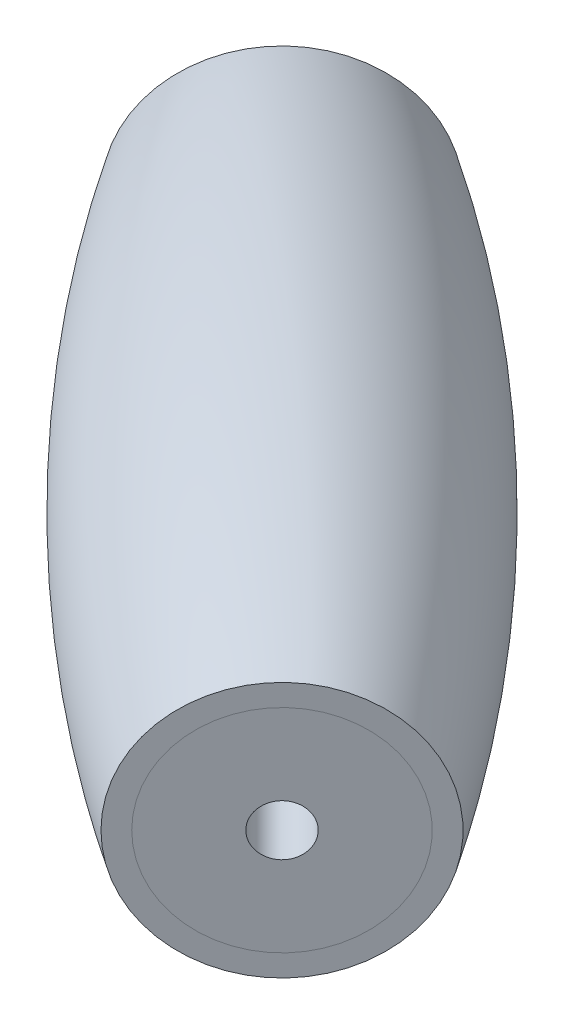
SolidWorks part; units mm, degrees
ref_plane "Front Plane" through (0, 0, 0) normal (0, 0, 1) x (1, 0, 0)
ref_plane "Top Plane" through (0, 0, 0) normal (0, 1, 0) x (1, 0, 0)
ref_plane "Right Plane" through (0, 0, 0) normal (1, 0, 0) x (0, 0, -1)
sketch "Sketch1" plane through (0, 0, 0) normal (0, 0, 1) x (1, 0, 0)
  line L0 (0, 66.7583) -> (0, -57.7369) construction
  line L1 (-59.5412, 0) -> (54.6439, 0) construction
  line L2 (0, 0) -> (-6.4705, 24.1481) construction
  line L3 (0, 0) -> (6.4705, 24.1481) construction
  circle A0 centre (0, 0) radius 25 construction
  dimension "D2" = 50
  dimension "D1" = 30
ref_plane "Plane1" through (0, 0, 0) normal (-0.7071, 0, 0.7071) x (0, -1, 0)
sketch "Sketch2" plane through (0, 0, 0) normal (-0.7071, 0, 0.7071) x (0, -1, 0)
  line L0 (-66.7583, 0) -> (57.7369, 0) construction
  line L1 (-66.7583, 0) -> (57.7369, 0) construction
  line L2 (0, -42.102) -> (0, 38.6391) construction
  line L3 (0, -42.102) -> (0, 38.6391) construction
  line L4 (-25, 0) -> (-25, 31.1188) construction
  line L5 (0, 35.355) -> (-11.3549, 35.355) construction
  line L6 (0, 0) -> (-24.1484, -9.149) construction
  line L7 (0, 0) -> (-24.1484, 9.149) construction
  line L8 (-24.1042, -9.1323) -> (-21.1042, -9.1323) construction
  line L9 (-21.1042, -9.1323) -> (-21.1042, 9.1323)
  line L10 (-24.1042, 9.1323) -> (-21.1042, 9.1323) construction
  line L11 (-23.6917, 8.6323) -> (-21.6042, 8.6323) construction
  line L12 (-21.6042, -8.6323) -> (-21.6042, 8.6323) construction
  line L13 (-23.6917, -8.6323) -> (-21.6042, -8.6323) construction
  line L14 (-23.5944, 9.1323) -> (-21.1042, 9.1323)
  line L15 (-23.5944, -9.1323) -> (-21.1042, -9.1323)
  arc A0 (-24.1042, -9.1323) -> (-24.1042, 9.1323) centre (22, 0) cw construction
  arc A1 (-23.5944, -9.1323) -> (-23.5944, 9.1323) centre (22, 0) cw
  arc A2 (-23.6917, -8.6323) -> (-23.6917, 8.6323) centre (22, 0) cw construction
  ellipse E0 centre (0, 0) end of major axis (0, 35.355) minor radius 25 construction
  point P22 (-21.1042, 0)
  dimension "D4" = 47
  dimension "D1" = 25
  dimension "D2" = 35.355
  dimension "D3" = 41.5
  dimension "D5" = 3
  dimension "D6" = 0.5
revolve "Revolve1" add sketch "Sketch2" angle 360 about L9
sketch "Sketch3" plane through (6.4575, 0, 6.4575) normal (0.7071, 0, 0.7071) x (0.7071, 0, -0.7071)
  circle A0 centre (0, 21.1042) radius 0.6
  circle A1 centre (0, 21.1042) radius 2.4902 construction
  dimension "D1" = 1.2
extrude "Cut-Extrude1" cut sketch "Sketch3" against normal through all
sketch "Sketch4" plane through (0, 0, 0) normal (-0.7071, 0, 0.7071) x (0.7071, 0, 0.7071)
  line L4 (-9.1323, 21.1042) -> (9.1323, 21.1042) construction
  line L5 (-9.1323, 21.1042) -> (9.1323, 21.1042) construction
  line L6 (-9.1323, 24.1042) -> (-9.1323, 23.5944)
  line L7 (9.1323, 23.5944) -> (9.1323, 24.1042)
  arc A0 (9.1323, 23.5944) -> (-9.1323, 23.5944) centre (0, -22) ccw construction
  arc A1 (9.1323, 24.1042) -> (-9.1323, 24.1042) centre (0, -22) ccw construction
  arc A2 (9.1323, 23.5944) -> (-9.1323, 23.5944) centre (0, -22) ccw
  arc A3 (9.1323, 24.1042) -> (-9.1323, 24.1042) centre (0, -22) ccw
revolve "Revolve4" add sketch "Sketch4" angle 360 about L5
